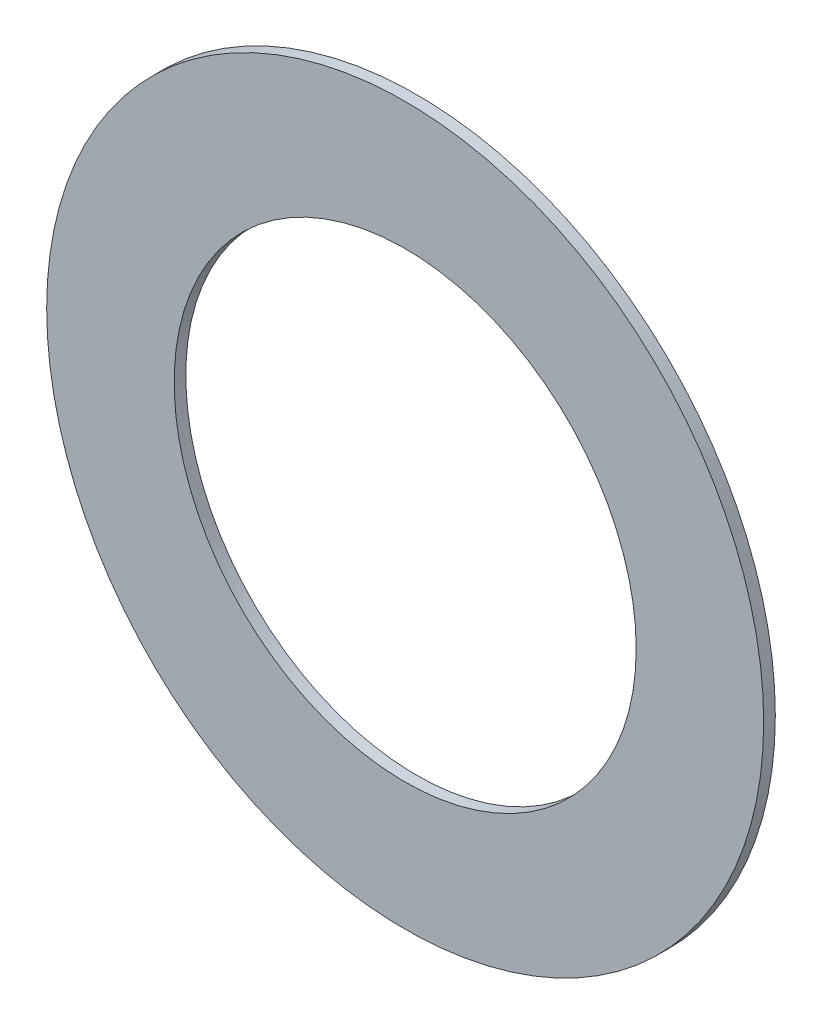
SolidWorks part; units mm, degrees
ref_plane "Front Plane" through (0, 0, 0) normal (0, 0, 1) x (1, 0, 0)
ref_plane "Top Plane" through (0, 0, 0) normal (0, 1, 0) x (1, 0, 0)
ref_plane "Right Plane" through (0, 0, 0) normal (1, 0, 0) x (0, 0, -1)
sketch "Sketch1" plane through (0, 0, 0) normal (0, 0, 1) x (1, 0, 0)
  circle A0 centre (0, 0) radius 7.0358
  circle A1 centre (0, 0) radius 4.5339
extrude "Extrude1" add sketch "Sketch1" along normal blind 0.2286
